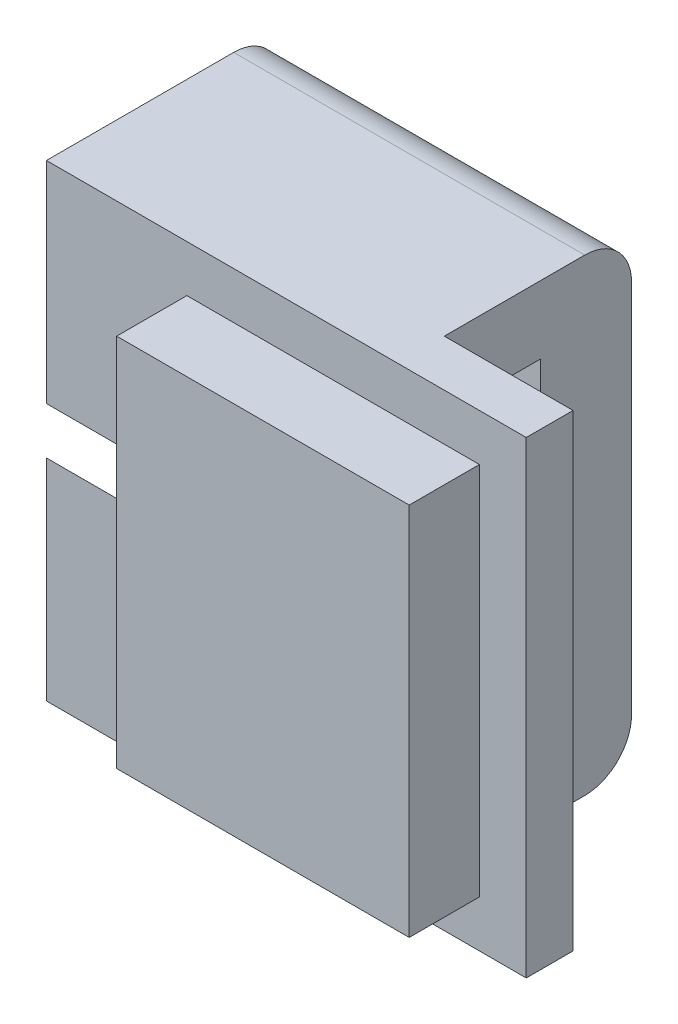
SolidWorks part; units mm, degrees
ref_plane "Front Plane" through (0, 0, 0) normal (1, 0, 0) x (0, 1, 0)
ref_plane "Top Plane" through (0, 0, 0) normal (0, 0, 1) x (0, 1, 0)
ref_plane "Right Plane" through (0, 0, 0) normal (0, 1, 0) x (-1, 0, 0)
sketch "Sketch1" plane through (0, 0, 0) normal (1, 0, 0) x (0, 1, 0)
  line L1 (-10, 5) -> (10, 5)
  line L2 (-10, 5) -> (-10, -5)
  line L3 (-10, -5) -> (10, -5)
  line L4 (10, 5) -> (10, -5)
  line L5 (-10, 5) -> (10, -5) construction
  line L6 (-10, -5) -> (10, 5) construction
  point P0 (0, 0)
  dimension "D1" = 10
  dimension "D2" = 20
extrude "Boss-Extrude1" add sketch "Sketch1" along normal blind 20.5
sketch "Sketch5" plane through (0, 0, 0) normal (0, 0, 1) x (0, 1, 0)
  line L1 (-8, -6) -> (8, -6)
  line L2 (-8, -6) -> (-8, -18.5)
  line L3 (-8, -18.5) -> (8, -18.5)
  line L4 (8, -6) -> (8, -18.5)
  line L5 (-10, -20.5) -> (-10, 0) construction
  line L6 (10, -20.5) -> (10, 0) construction
  line L7 (10, -20.5) -> (-10, -20.5) construction
  line L8 (10, 0) -> (-10, 0) construction
  dimension "D1" = 2
  dimension "D2" = 2
  dimension "D3" = 2
  dimension "D4" = 6
extrude "Boss-Extrude2" add sketch "Sketch5" along normal blind 8
sketch "Sketch2" plane through (0, 0, 0) normal (1, 0, 0) x (0, 1, 0)
  circle A0 centre (0, 0) radius 5.1
  dimension "D1" = 10.2
extrude "Cut-Extrude3" cut sketch "Sketch2" along normal blind 10
sketch "Sketch6" plane through (0, 0, -5) normal (0, 0, -1) x (1, 0, 0)
  line L2 (20.5, -10) -> (0, -10) construction
  line L3 (20.5, 10) -> (15, 10)
  line L4 (20.5, 10) -> (20.5, -10)
  line L5 (20.5, -10) -> (15, -10)
  line L6 (15, 10) -> (15, -10)
  line L7 (10, 1.005) -> (10, -1.005) construction
  dimension "D1" = 5
extrude "Cut-Extrude4" cut sketch "Sketch6" against normal blind 8
sketch "Sketch7" plane through (15, 0, 0) normal (1, 0, 0) x (0, 1, 0)
  line L0 (0, 0) -> (6, 0) construction
  line L1 (0, -7.15) -> (0, 7.15) construction
  line L2 (4.9, 1.1) -> (7.1, 1.1)
  line L3 (4.9, 1.1) -> (4.9, -1.1)
  line L4 (4.9, -1.1) -> (7.1, -1.1)
  line L5 (7.1, 1.1) -> (7.1, -1.1)
  line L6 (4.9, 1.1) -> (7.1, -1.1) construction
  line L7 (4.9, -1.1) -> (7.1, 1.1) construction
  line L8 (-4.9, -1.1) -> (-7.1, -1.1)
  line L9 (-7.1, 1.1) -> (-7.1, -1.1)
  line L10 (-4.9, 1.1) -> (-7.1, 1.1)
  line L11 (-4.9, 1.1) -> (-4.9, -1.1)
  dimension "D1" = 6
  dimension "D2" = 2.2
  dimension "D3" = 2.2
extrude "Cut-Extrude5" cut sketch "Sketch7" against normal blind 3
fillet "Fillet1" radius 2 2 edges at (7.5, 10, -5) (7.5, -10, -5)
